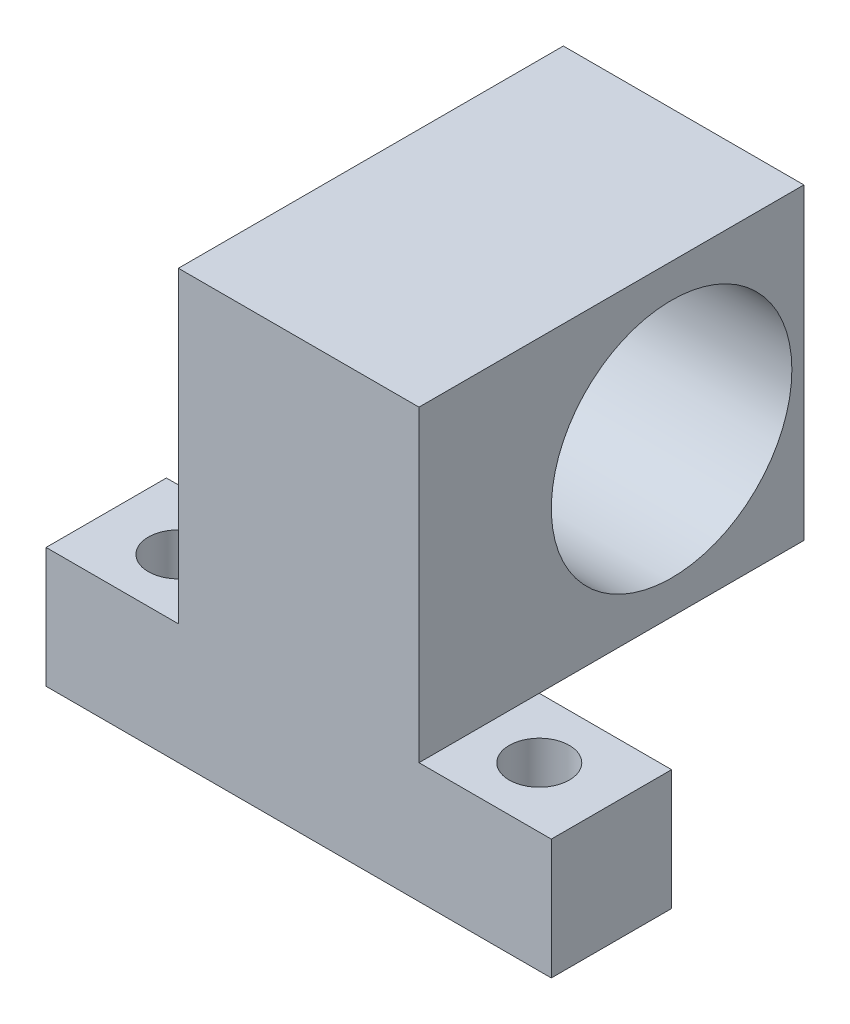
SolidWorks part; units mm, degrees
ref_plane "Front Plane" through (0, 0, 0) normal (0, 0, 1) x (1, 0, 0)
ref_plane "Top Plane" through (0, 0, 0) normal (0, 1, 0) x (1, 0, 0)
ref_plane "Right Plane" through (0, 0, 0) normal (1, 0, 0) x (0, 0, -1)
sketch "Sketch1" plane through (0, 0, 0) normal (0, 0, 1) x (1, 0, 0)
  line L1 (0, 0) -> (21, 0)
  line L2 (0, 0) -> (0, 5)
  line L3 (0, 5) -> (21, 5)
  line L4 (21, 0) -> (21, 5)
  dimension "D1" = 21
  dimension "D2" = 5
extrude "Boss-Extrude1" add sketch "Sketch1" along normal blind 5
sketch "Sketch2" plane through (0, 5, 0) normal (0, 1, 0) x (1, 0, 0)
  line L0 (21, -5) -> (0, -5) construction
  line L1 (5.5, -5) -> (15.5, -5)
  line L2 (5.5, -5) -> (5.5, 11)
  line L3 (5.5, 11) -> (15.5, 11)
  line L4 (15.5, -5) -> (15.5, 11)
  line L5 (21, -5) -> (0, -5) construction
  point P6 (10.5, -5)
  point P7 (10.5, -5)
  dimension "D1" = 10
  dimension "D2" = 16
extrude "Boss-Extrude2" add sketch "Sketch2" along normal blind 12.8
sketch "Sketch3" plane through (0, 5, 0) normal (0, 1, 0) x (1, 0, 0)
  line L0 (0, -5) -> (0, 0) construction
  line L1 (5.5, 0) -> (0, 0) construction
  line L2 (0, -5) -> (0, 0) construction
  line L3 (5.5, 0) -> (0, 0) construction
  line L4 (10.5, -5) -> (10.5, -2.5) construction
  line L5 (5.5, -5) -> (15.5, -5) construction
  circle A0 centre (3, -2.5) radius 1.25
  circle A1 centre (18, -2.5) radius 1.25
  point P6 (0, -2.5)
  point P13 (0, 0)
  dimension "D1" = 2.5
  dimension "D2" = 15
extrude "Cut-Extrude1" cut sketch "Sketch3" against normal blind 13
sketch "Sketch4" plane through (15.5, 0, 0) normal (1, 0, 0) x (0, 0, -1)
  line L0 (11, 17.8) -> (11, 5) construction
  line L1 (0, 5) -> (11, 5) construction
  line L2 (0, 5) -> (11, 5) construction
  circle A0 centre (5.5, 11.4) radius 5
  point P2 (5.1205, 11.4494)
  point P3 (0, 0)
  point P6 (11, 11.4)
  point P7 (4.7964, 11.4)
  point P8 (5.0015, 11.4)
  point P11 (5.5, 5)
  dimension "D1" = 10
extrude "Cut-Extrude2" cut sketch "Sketch4" against normal blind 13
